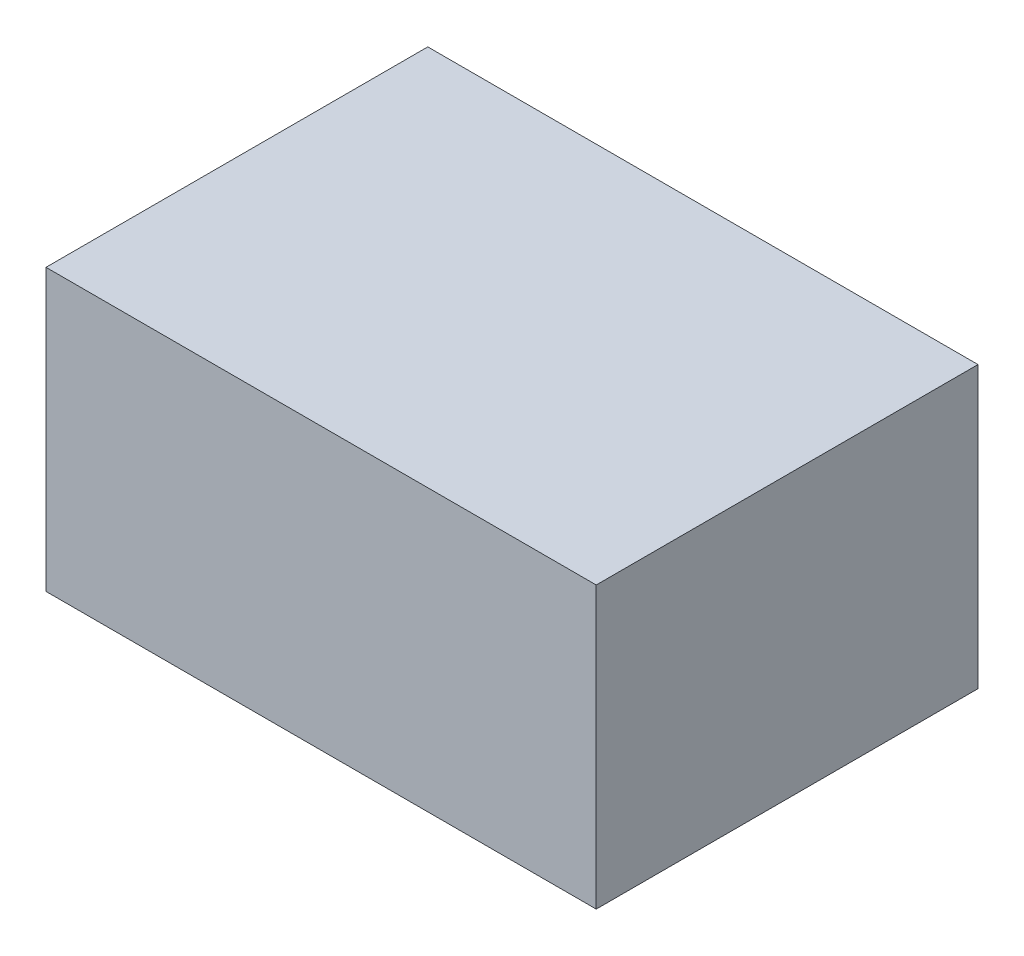
SolidWorks part; units mm, degrees
ref_plane "Front Plane" through (0, 0, 0) normal (0, 0, 1) x (1, 0, 0)
ref_plane "Top Plane" through (0, 0, 0) normal (0, 1, 0) x (1, 0, 0)
ref_plane "Right Plane" through (0, 0, 0) normal (1, 0, 0) x (0, 0, -1)
sketch "Sketch1" plane through (0, 0, 0) normal (0, 0, 1) x (1, 0, 0)
  line L1 (24.5, 12.5) -> (-24.5, 12.5)
  line L2 (24.5, 12.5) -> (24.5, -12.5)
  line L3 (24.5, -12.5) -> (-24.5, -12.5)
  line L4 (-24.5, 12.5) -> (-24.5, -12.5)
  line L5 (24.5, 12.5) -> (-24.5, -12.5) construction
  line L6 (24.5, -12.5) -> (-24.5, 12.5) construction
  point P0 (0, 0)
  dimension "D1" = 49
  dimension "D2" = 25
extrude "Boss-Extrude1" add sketch "Sketch1" along normal blind 34
